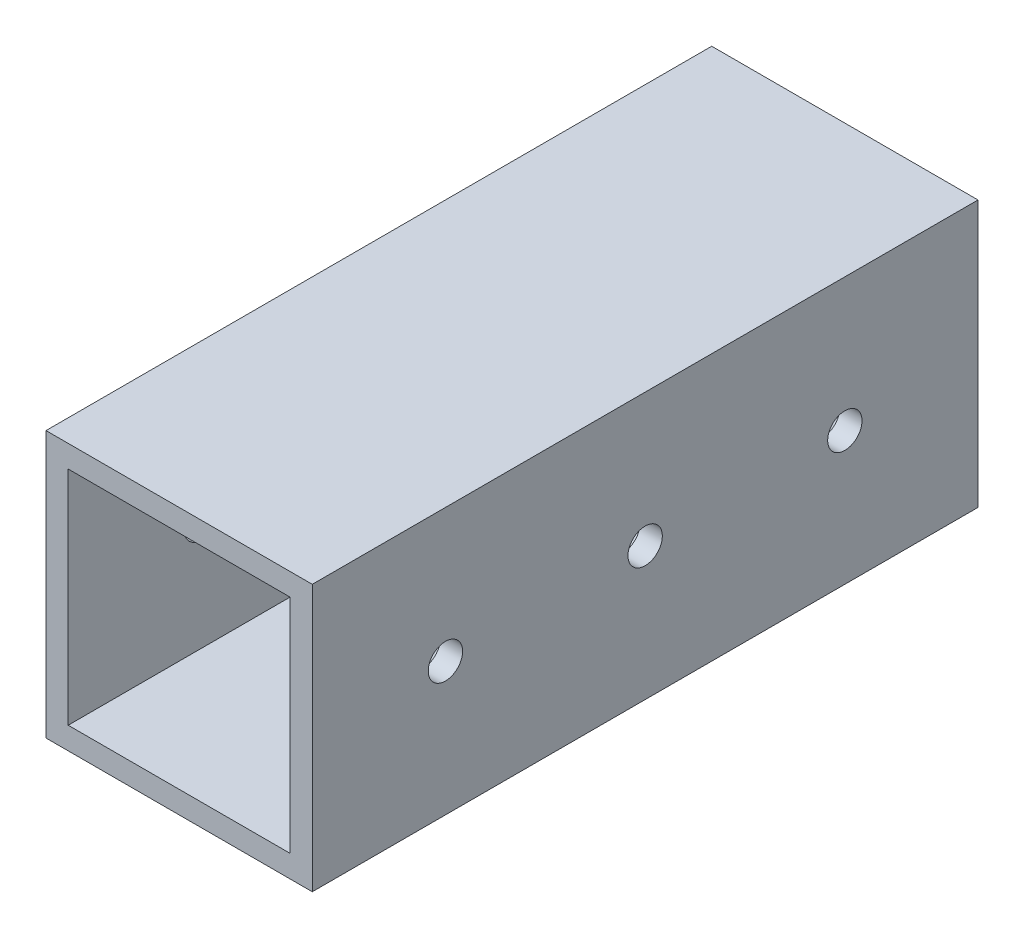
SolidWorks part; units mm, degrees
material "6061 Alloy"
ref_plane "Front Plane" through (0, 0, 0) normal (0, 0, 1) x (1, 0, 0)
ref_plane "Top Plane" through (0, 0, 0) normal (0, 1, 0) x (1, 0, 0)
ref_plane "Right Plane" through (0, 0, 0) normal (1, 0, 0) x (0, 0, -1)
sketch "Sketch1" plane through (0, 0, 0) normal (0, 0, 1) x (1, 0, 0)
  line L0 (-15.875, 15.875) -> (15.875, 15.875)
  line L1 (-19.05, -19.05) -> (19.05, -19.05)
  line L2 (-19.05, -19.05) -> (-19.05, 19.05)
  line L3 (-19.05, 19.05) -> (19.05, 19.05)
  line L4 (19.05, -19.05) -> (19.05, 19.05)
  line L5 (-19.05, -19.05) -> (19.05, 19.05) construction
  line L6 (-19.05, 19.05) -> (19.05, -19.05) construction
  line L7 (15.875, -15.875) -> (15.875, 15.875)
  line L8 (-15.875, -15.875) -> (15.875, -15.875)
  line L9 (-15.875, -15.875) -> (-15.875, 15.875)
  point P0 (0, 0)
  dimension "D1" = 38.1
  dimension "D2" = 38.1
  dimension "D3" = 3.175
extrude "Boss-Extrude1" add sketch "Sketch1" along normal blind 95.25
sketch "Sketch2" plane through (19.05, 0, 0) normal (-1, 0, 0) x (0, 1, 0)
  line L0 (0, 0) -> (0, -95.25) construction
  line L1 (-19.05, 0) -> (19.05, 0) construction
  line L3 (-19.05, -95.25) -> (19.05, -95.25) construction
  line L4 (-19.05, -47.625) -> (19.05, -47.625) construction
  line L5 (-19.05, -95.25) -> (-19.05, 0) construction
  line L6 (19.05, -95.25) -> (19.05, 0) construction
  line L7 (19.05, -95.25) -> (-19.05, -95.25) construction
  point P0 (0, -19.05)
  point P1 (0, -76.2)
  dimension "D1" = 19.05
hole_wizard "#10 (0.1935) Diameter Hole1" positions "3DSketch1" profile "Sketch3" hole size "#10" standard "ANSI Inch" end condition through all
sketch3d "3DSketch1"
  line L0 (19.05, 0, 19.05) -> (19.05, 0, 76.2) construction
  point P0 (19.05, 0, 19.05)
  point P3 (19.05, 0, 76.2)
  point P6 (19.05, 0, 47.625)
sketch "Sketch3" plane through (19.05, 0, 19.05) normal (0, 1, 0) x (0, 0, -1)
  line L0 (0, 0) -> (0, 38.1)
  line L1 (0, 38.1) -> (2.4574, 38.1)
  line L2 (2.4574, 38.1) -> (2.4574, 0)
  line L5 (2.4574, 0) -> (0, 0)
  line L11 (0, -6.35) -> (0, 107.95) construction
  dimension "Thru Hole Dia." = 4.9149
  dimension "Thru Hole Depth" = 38.1
